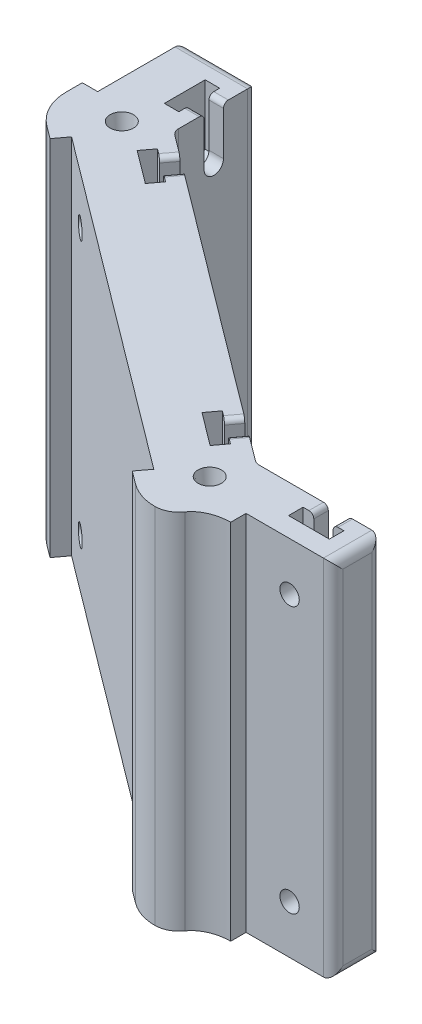
SolidWorks part; units mm, degrees
ref_plane "Front Plane" through (0, 0, 0) normal (0, 0, 1) x (1, 0, 0)
ref_plane "Top Plane" through (0, 0, 0) normal (0, 1, 0) x (1, 0, 0)
ref_plane "Right Plane" through (0, 0, 0) normal (1, 0, 0) x (0, 0, -1)
sketch "Sketch1" plane through (0, 0, 0) normal (0, 1, 0) x (1, 0, 0)
  line L0 (0, -10) -> (0, -6.825) construction
  line L2 (28.6667, -1.825) -> (28.6667, 86) construction
  line L3 (-6, -8) -> (-4.095, -5.46) construction
  line L6 (-4.095, -5.46) -> (0, 0) construction
  line L7 (0, -10) -> (-3.3333, -10) construction
  line L8 (0, 0) -> (0, -6.825) construction
  line L9 (-3.1623, -9.4868) -> (0, 0) construction
  line L10 (0, 0) -> (28.6667, 86) construction
  line L12 (-18.0283, 23.74) -> (2.725, 8.175)
  line L13 (28.6667, -1.825) -> (28.6667, 8.175)
  line L14 (28.6667, 8.175) -> (2.725, 8.175)
  line L15 (-6, -8) -> (-8.6667, -6)
  line L16 (-8.6667, -6) -> (-6.7617, -3.46)
  line L18 (10.6667, -5) -> (10.6667, -1.825)
  line L19 (-74.7617, 47.54) -> (-6.7617, -3.46)
  line L20 (-6.7617, -3.46) -> (-4.095, -5.46) construction
  line L22 (10.6667, -1.825) -> (28.6667, -1.825)
  line L23 (-6, -8) -> (-79.3333, 47) construction
  line L24 (-3.3333, -10) -> (-6, -8) construction
  line L25 (-8.6667, -6) -> (-83.3333, 50) construction
  line L26 (-74.7617, 47.54) -> (-76.6667, 45)
  line L27 (-76.6667, 45) -> (-79.3333, 47)
  line L28 (-83.3333, 50) -> (-83.3333, 76.3333) construction
  line L29 (-83.3333, 55) -> (-83.3333, 58.3333)
  line L30 (-83.3333, 58.3333) -> (-80.1583, 58.3333)
  line L31 (-80.1583, 58.3333) -> (-80.1583, 76.3333)
  line L32 (28.6667, 86) -> (-27.0283, 11.74) construction
  line L33 (-80.1583, 76.3333) -> (-65.1583, 76.3333)
  line L34 (-65.1583, 76.3333) -> (-65.1583, 59.0875)
  line L35 (-82.2776, 50.5279) -> (-65.1583, 59.0875) construction
  line L36 (-65.1583, 59.0875) -> (-51.3617, 48.74)
  line L37 (-51.3617, 48.74) -> (-60.3617, 36.74) construction
  line L38 (-51.3617, 48.74) -> (-18.0283, 23.74)
  line L39 (-83.3333, 76.3333) -> (-80.1583, 76.3333) construction
  arc A0 (0, -10) -> (-6, -8) centre (0, 0) cw
  arc A1 (-83.3333, 55) -> (-79.3333, 47) centre (-73.3333, 55) ccw
  arc A2 (0, -10) -> (4.1098, -7.8477) centre (0, -5) ccw
  ellipse E0 centre (10.6667, -10) end of major axis (3.4023, -10) minor radius 5 (4.1098, -7.8477) -> (10.6667, -5) cw
  point P34 (-83.5101, 58.4659)
  point P44 (10, -8.3109)
  point P45 (0, 0)
  point P46 (12.6511, -5)
  dimension "D1" = 10
  dimension "D3" = 60
  dimension "D7" = 3.3333
  dimension "D8" = 5
  dimension "D9" = 3.175
  dimension "D2" = 15
  dimension "D4" = 18
  dimension "D5" = 10.6667
  dimension "D6" = 5
  dimension "D10" = 3.175
  dimension "D11" = 80
  dimension "D12" = 18
extrude "Boss-Extrude1" add sketch "Sketch1" along normal blind 75
sketch "Sketch2" plane through (0, 0, 1.825) normal (0, 0, 1) x (1, 0, 0)
  line L0 (19.6667, 0) -> (19.6667, 75) construction
  line L1 (10.6667, 0) -> (28.6667, 0) construction
  line L2 (10.6667, 75) -> (28.6667, 75) construction
  circle A0 centre (19.6667, 10) radius 2
  circle A1 centre (19.6667, 65) radius 2
  dimension "D1" = 4
  dimension "D2" = 10
  dimension "D3" = 10
extrude "Cut-Extrude1" cut sketch "Sketch2" against normal up to surface (10 mm away) up to face at (15.6958, 37.5, -8.175)
sketch "Sketch3" plane through (-4.095, 0, 5.46) normal (-0.6, 0, 0.8) x (0.8, 0, 0.6)
  line L0 (-12.3333, 0) -> (-12.3333, 75) construction
  line L1 (-88.3333, 0) -> (-3.3333, 0) construction
  line L2 (-88.3333, 75) -> (-3.3333, 75) construction
  line L3 (-3.3333, 75) -> (-3.3333, 0) construction
  line L4 (-45.8333, 0) -> (-45.8333, 75) construction
  line L5 (-88.3333, 0) -> (-3.3333, 0) construction
  line L6 (-88.3333, 75) -> (-3.3333, 75) construction
  circle A0 centre (-12.3333, 10) radius 2
  circle A1 centre (-12.3333, 65) radius 2
  circle A2 centre (-79.3333, 10) radius 2
  circle A3 centre (-79.3333, 65) radius 2
  dimension "D1" = 4
  dimension "D3" = 10
  dimension "D2" = 10
  dimension "D4" = 9
extrude "Cut-Extrude2" cut sketch "Sketch3" against normal up to surface (15 mm away) up to face at (-31.2167, 37.5, -33.6312)
sketch "Sketch4" plane through (-80.1583, 0, 0) normal (-1, 0, 0) x (0, 0, 1)
  line L0 (-67.3333, 0) -> (-67.3333, 75) construction
  line L1 (-76.3333, 0) -> (-58.3333, 0) construction
  line L2 (-76.3333, 75) -> (-58.3333, 75) construction
  circle A0 centre (-67.3333, 10) radius 2
  circle A1 centre (-67.3333, 65) radius 2
  dimension "D1" = 4
  dimension "D2" = 10
  dimension "D3" = 10
extrude "Cut-Extrude3" cut sketch "Sketch4" against normal up to surface (15 mm away) up to face at (-65.1583, 37.5, -67.7104)
sketch "Sketch6" plane through (4.905, 0, -6.54) normal (0.6, 0, -0.8) x (-0.8, 0, -0.6)
  line L0 (8.1146, 62.5643) -> (12.3333, 60.1286)
  line L1 (12.3333, 60.1286) -> (16.5521, 62.5643) construction
  line L2 (16.5521, 62.5643) -> (16.5521, 67.4357) construction
  line L3 (16.5521, 67.4357) -> (12.3333, 69.8714) construction
  line L4 (12.3333, 69.8714) -> (8.1146, 67.4357) construction
  line L5 (8.1146, 67.4357) -> (8.1146, 62.5643) construction
  line L6 (8.1146, 62.5643) -> (12.3333, 60.1286) construction
  line L7 (12.3333, 5.1286) -> (16.5521, 7.5643) construction
  line L8 (16.5521, 7.5643) -> (16.5521, 12.4357) construction
  line L9 (16.5521, 12.4357) -> (12.3333, 14.8714) construction
  line L10 (12.3333, 14.8714) -> (8.1146, 12.4357) construction
  line L11 (8.1146, 12.4357) -> (8.1146, 7.5643) construction
  line L12 (8.1146, 7.5643) -> (12.3333, 5.1286) construction
  line L13 (79.3333, 5.1286) -> (83.5521, 7.5643) construction
  line L14 (83.5521, 7.5643) -> (83.5521, 12.4357) construction
  line L15 (83.5521, 12.4357) -> (79.3333, 14.8714) construction
  line L16 (79.3333, 14.8714) -> (75.1146, 12.4357) construction
  line L17 (75.1146, 12.4357) -> (75.1146, 7.5643) construction
  line L18 (75.1146, 7.5643) -> (79.3333, 5.1286) construction
  line L19 (79.3333, 60.1286) -> (83.5521, 62.5643) construction
  line L20 (83.5521, 62.5643) -> (83.5521, 67.4357) construction
  line L21 (83.5521, 67.4357) -> (79.3333, 69.8714) construction
  line L22 (79.3333, 69.8714) -> (75.1146, 67.4357) construction
  line L23 (75.1146, 67.4357) -> (75.1146, 62.5643) construction
  line L24 (75.1146, 62.5643) -> (79.3333, 60.1286) construction
  line L25 (12.3333, 60.1286) -> (16.5521, 62.5643)
  line L26 (16.5521, 62.5643) -> (16.5521, 75)
  line L27 (2.725, 75) -> (87.5792, 75) construction
  line L28 (16.5521, 75) -> (8.1146, 75)
  line L29 (8.1146, 75) -> (8.1146, 62.5643)
  line L30 (75.1146, 62.5643) -> (79.3333, 60.1286)
  line L31 (79.3333, 60.1286) -> (83.5521, 62.5643)
  line L32 (83.5521, 62.5643) -> (83.5521, 75)
  line L33 (83.5521, 75) -> (75.1146, 75)
  line L34 (75.1146, 75) -> (75.1146, 62.5643)
  line L35 (8.1146, 12.4357) -> (12.3333, 14.8714)
  line L36 (12.3333, 14.8714) -> (16.5521, 12.4357)
  line L37 (16.5521, 12.4357) -> (16.5521, 0)
  line L38 (2.725, 0) -> (87.5792, 0) construction
  line L39 (16.5521, 0) -> (8.1146, 0)
  line L40 (8.1146, 0) -> (8.1146, 12.4357)
  line L41 (75.1146, 12.4357) -> (79.3333, 14.8714)
  line L42 (79.3333, 14.8714) -> (83.5521, 12.4357)
  line L43 (83.5521, 12.4357) -> (83.5521, 0)
  line L44 (83.5521, 0) -> (75.1146, 0)
  line L45 (75.1146, 0) -> (75.1146, 12.4357)
  circle A0 centre (12.3333, 65) radius 4.2187 construction
  circle A1 centre (12.3333, 10) radius 4.2188 construction
  circle A2 centre (79.3333, 10) radius 4.2187 construction
  circle A3 centre (79.3333, 65) radius 4.2187 construction
  dimension "D1" = 8.4375
extrude "Cut-Extrude5" cut sketch "Sketch6" against normal blind 3 from offset 3 offset against normal yes
sketch "Sketch7" plane through (4.905, 0, -6.54) normal (0.6, 0, -0.8) x (-0.8, 0, -0.6)
  line L0 (14.3333, 65) -> (14.3333, 75)
  line L1 (2.725, 75) -> (87.5792, 75) construction
  line L2 (14.3333, 75) -> (10.3333, 75)
  line L3 (10.3333, 75) -> (10.3333, 65)
  line L4 (81.3333, 65) -> (81.3333, 75)
  line L5 (81.3333, 0) -> (77.3333, 0)
  line L6 (2.725, 37.5) -> (87.5792, 37.5) construction
  line L7 (2.725, 75) -> (2.725, 0) construction
  line L8 (87.5792, 75) -> (87.5792, 0) construction
  line L18 (81.3333, 75) -> (77.3333, 75)
  line L19 (77.3333, 75) -> (77.3333, 65)
  line L20 (81.3333, 10) -> (81.3333, 0)
  line L21 (77.3333, 0) -> (77.3333, 10)
  line L22 (14.3333, 0) -> (10.3333, 0)
  line L23 (14.3333, 10) -> (14.3333, 0)
  line L24 (10.3333, 0) -> (10.3333, 10)
  arc A0 (10.3333, 65) -> (14.3333, 65) centre (12.3333, 65) cw
  circle A1 centre (12.3333, 65) radius 2 construction
  arc A5 (77.3333, 65) -> (81.3333, 65) centre (79.3333, 65) cw
  circle A6 centre (79.3333, 65) radius 2 construction
  arc A7 (77.3333, 10) -> (81.3333, 10) centre (79.3333, 10) ccw
  arc A8 (10.3333, 10) -> (14.3333, 10) centre (12.3333, 10) ccw
extrude "Cut-Extrude6" cut sketch "Sketch7" against normal blind 3
sketch "Sketch8" plane through (0, 0, -8.175) normal (0, 0, -1) x (-1, 0, 0)
  line L0 (-23.8854, 0) -> (-23.8854, 12.4357)
  line L1 (-19.6667, 60.1286) -> (-15.4479, 62.5643) construction
  line L2 (-15.4479, 62.5643) -> (-15.4479, 67.4357) construction
  line L3 (-15.4479, 67.4357) -> (-19.6667, 69.8714) construction
  line L4 (-19.6667, 69.8714) -> (-23.8854, 67.4357) construction
  line L5 (-23.8854, 67.4357) -> (-23.8854, 62.5643) construction
  line L6 (-23.8854, 62.5643) -> (-19.6667, 60.1286) construction
  line L7 (-19.6667, 5.1286) -> (-15.4479, 7.5643) construction
  line L8 (-15.4479, 7.5643) -> (-15.4479, 12.4357) construction
  line L9 (-15.4479, 12.4357) -> (-19.6667, 14.8714) construction
  line L10 (-19.6667, 14.8714) -> (-23.8854, 12.4357) construction
  line L11 (-23.8854, 12.4357) -> (-23.8854, 7.5643) construction
  line L12 (-23.8854, 7.5643) -> (-19.6667, 5.1286) construction
  line L13 (-28.6667, 0) -> (-2.725, 0) construction
  line L14 (-23.8854, 12.4357) -> (-19.6667, 14.8714)
  line L15 (-19.6667, 14.8714) -> (-15.4479, 12.4357)
  line L16 (-15.4479, 12.4357) -> (-15.4479, 0)
  line L17 (-15.4479, 0) -> (-23.8854, 0)
  line L18 (-23.8854, 62.5643) -> (-19.6667, 60.1286)
  line L19 (-19.6667, 60.1286) -> (-15.4479, 62.5643)
  line L20 (-15.4479, 62.5643) -> (-15.4479, 75)
  line L21 (-28.6667, 75) -> (-2.725, 75) construction
  line L22 (-15.4479, 75) -> (-23.8854, 75)
  line L23 (-23.8854, 75) -> (-23.8854, 62.5643)
  circle A0 centre (-19.6667, 65) radius 4.2187 construction
  circle A1 centre (-19.6667, 10) radius 4.2188 construction
  dimension "D1" = 8.4375
extrude "Cut-Extrude7" cut sketch "Sketch8" against normal blind 3 from offset 3 offset against normal yes
sketch "Sketch9" plane through (0, 0, -8.175) normal (0, 0, -1) x (-1, 0, 0)
  line L0 (-17.6667, 65) -> (-17.6667, 75)
  line L1 (-28.6667, 75) -> (-2.725, 75) construction
  line L2 (-17.6667, 75) -> (-21.6667, 75)
  line L3 (-21.6667, 75) -> (-21.6667, 65)
  line L4 (-21.6667, 10) -> (-21.6667, 0)
  line L5 (-28.6667, 0) -> (-2.725, 0) construction
  line L6 (-21.6667, 0) -> (-17.6667, 0)
  line L7 (-17.6667, 0) -> (-17.6667, 10)
  arc A0 (-21.6667, 65) -> (-17.6667, 65) centre (-19.6667, 65) cw
  circle A1 centre (-19.6667, 65) radius 2 construction
  arc A2 (-21.6667, 10) -> (-17.6667, 10) centre (-19.6667, 10) ccw
  circle A3 centre (-19.6667, 10) radius 2 construction
extrude "Cut-Extrude8" cut sketch "Sketch9" against normal blind 3
sketch "Sketch10" plane through (-65.1583, 0, 0) normal (1, 0, 0) x (0, 0, -1)
  line L0 (63.1146, 62.5643) -> (67.3333, 60.1286)
  line L1 (67.3333, 60.1286) -> (71.5521, 62.5643) construction
  line L2 (71.5521, 62.5643) -> (71.5521, 67.4357) construction
  line L3 (71.5521, 67.4357) -> (67.3333, 69.8714) construction
  line L4 (67.3333, 69.8714) -> (63.1146, 67.4357) construction
  line L5 (63.1146, 67.4357) -> (63.1146, 62.5643) construction
  line L6 (63.1146, 62.5643) -> (67.3333, 60.1286) construction
  line L7 (67.3333, 5.1286) -> (71.5521, 7.5643) construction
  line L8 (71.5521, 7.5643) -> (71.5521, 12.4357) construction
  line L9 (71.5521, 12.4357) -> (67.3333, 14.8714) construction
  line L10 (67.3333, 14.8714) -> (63.1146, 12.4357) construction
  line L11 (63.1146, 12.4357) -> (63.1146, 7.5643) construction
  line L12 (63.1146, 7.5643) -> (67.3333, 5.1286) construction
  line L13 (67.3333, 60.1286) -> (71.5521, 62.5643)
  line L14 (71.5521, 62.5643) -> (71.5521, 75)
  line L15 (59.0875, 75) -> (76.3333, 75) construction
  line L16 (71.5521, 75) -> (63.1146, 75)
  line L17 (63.1146, 75) -> (63.1146, 62.5643)
  line L18 (63.1146, 12.4357) -> (67.3333, 14.8714)
  line L19 (67.3333, 14.8714) -> (71.5521, 12.4357)
  line L20 (71.5521, 12.4357) -> (71.5521, 0)
  line L21 (59.0875, 0) -> (76.3333, 0) construction
  line L22 (71.5521, 0) -> (63.1146, 0)
  line L23 (63.1146, 0) -> (63.1146, 12.4357)
  circle A0 centre (67.3333, 65) radius 4.2188 construction
  circle A1 centre (67.3333, 10) radius 4.2188 construction
  dimension "D1" = 8.4375
extrude "Cut-Extrude9" cut sketch "Sketch10" against normal blind 3 from offset 3 offset against normal yes
sketch "Sketch5" plane through (0, 75, 0) normal (0, 1, 0) x (1, 0, 0)
  line L0 (-3.1623, -9.4868) -> (2.725, 8.175) construction
  line L1 (-82.2776, 50.5279) -> (-65.1583, 59.0875) construction
  line L2 (-72.3333, 55.5) -> (0.3333, 1) construction
  line L3 (-74.7617, 47.54) -> (-6.7617, -3.46) construction
  line L4 (-8.6667, -6) -> (-6, -8) construction
  arc A0 (-6, -8) -> (0, -10) centre (0, 0) ccw construction
  arc A1 (-83.3333, 55) -> (-79.3333, 47) centre (-73.3333, 55) ccw construction
  circle A2 centre (0.3333, 1) radius 2.413
  circle A3 centre (-72.3333, 55.5) radius 2.413
  dimension "D1" = 4.826
  dimension "D2" = 11
extrude "Cut-Extrude4" cut sketch "Sketch5" against normal blind 6.35 draft 8 contours A2 | A3
sketch "Sketch11" plane through (-65.1583, 0, 0) normal (1, 0, 0) x (0, 0, -1)
  line L0 (69.3333, 65) -> (69.3333, 75)
  line L1 (59.0875, 75) -> (76.3333, 75) construction
  line L2 (69.3333, 75) -> (65.3333, 75)
  line L3 (65.3333, 75) -> (65.3333, 65)
  line L4 (69.3333, 10) -> (69.3333, 0)
  line L5 (59.0875, 0) -> (76.3333, 0) construction
  line L6 (69.3333, 0) -> (65.3333, 0)
  line L7 (65.3333, 0) -> (65.3333, 10)
  arc A0 (65.3333, 65) -> (69.3333, 65) centre (67.3333, 65) cw
  circle A1 centre (67.3333, 65) radius 2 construction
  arc A2 (65.3333, 10) -> (69.3333, 10) centre (67.3333, 10) ccw
  circle A3 centre (67.3333, 10) radius 2 construction
extrude "Cut-Extrude10" cut sketch "Sketch11" against normal blind 3
sketch "Sketch14" plane through (0, 68.65, 0) normal (0, 1, 0) x (1, 0, 0)
  circle A0 centre (-72.3333, 55.5) radius 1.5206
  circle A1 centre (0.3333, 1) radius 1.5206
  circle A2 centre (-72.3333, 55.5) radius 1.5206 construction
extrude "Cut-Extrude12" cut sketch "Sketch14" against normal blind 5
ref_plane "Plane1" through (0, 37.5, 0) normal (0, 1, 0) x (1, 0, 0)
mirror "Mirror1" about plane through (0, 37.5, 0) normal (0, 1, 0) of "Cut-Extrude4", "Cut-Extrude12"
fillet "Fillet1" radius 1 16 edges at (-66.6583, 75, -69.3333) (-66.6583, 75, -65.3333) (-57.8617, 75, -51.74) (-61.0617, 75, -54.14) (-66.6583, 0, -69.3333) (-66.6583, 0, -65.3333) (-61.0617, 0, -54.14) (-57.8617, 0, -51.74) (-7.4617, 0, -13.94) (-4.2617, 0, -11.54) (21.6667, 0, -6.675) (17.6667, 0, -6.675) (-7.4617, 75, -13.94) (-4.2617, 75, -11.54) (17.6667, 75, -6.675) (21.6667, 75, -6.675)
fillet "Fillet2" radius 2 10 edges at (28.6667, 75, -3.175) (-72.6583, 75, -76.3333) (-72.6583, 0, -76.3333) (28.6667, 0, -3.175) (-80.1583, 37.5, -76.3333) (-65.1583, 37.5, -76.3333) (-65.1583, 37.5, -59.0875) (2.725, 37.5, -8.175) (28.6667, 37.5, -8.175) (28.6667, 37.5, 1.825)
equation "\"0.25i\"=3"
